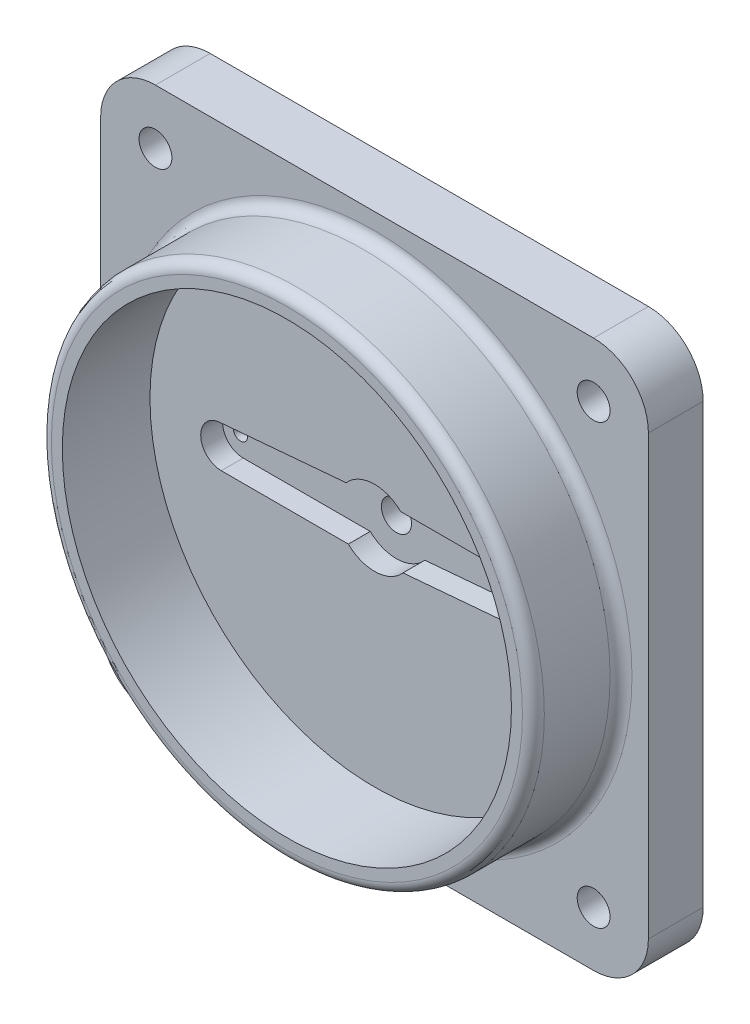
SolidWorks part; units mm, degrees
ref_plane "Plan de face" through (0, 0, 0) normal (0, 0, 1) x (1, 0, 0)
ref_plane "Plan de dessus" through (0, 0, 0) normal (0, 1, 0) x (1, 0, 0)
ref_plane "Plan de droite" through (0, 0, 0) normal (1, 0, 0) x (0, 0, -1)
sketch "Esquisse1" plane through (0, 0, 0) normal (0, 0, 1) x (1, 0, 0)
  line L1 (-25, 25) -> (25, 25)
  line L2 (-25, 25) -> (-25, -25)
  line L3 (-25, -25) -> (25, -25)
  line L4 (25, 25) -> (25, -25)
  line L5 (-25, 25) -> (25, -25) construction
  line L6 (-25, -25) -> (25, 25) construction
  point P0 (0, 0)
  dimension "D1" = 50
  dimension "D2" = 50
extrude "Boss.-Extru.3" add sketch "Esquisse1" along normal blind 5
sketch "Esquisse3" plane through (0, 0, 5) normal (0, 0, 1) x (1, 0, 0)
  circle A0 centre (0, 0) radius 22.5
  circle A1 centre (0, 0) radius 20.5
  dimension "D1" = 45
  dimension "D2" = 2
extrude "Boss.-Extru.4" add sketch "Esquisse3" along normal blind 8
sketch "Esquisse4" plane through (0, 0, 5) normal (0, 0, 1) x (1, 0, 0)
  line L0 (-14.1481, 1.2731) -> (-2.5947, 2.2661)
  line L1 (-13.9871, -2.48) -> (-2.3912, -2.48)
  line L2 (13.9871, 2.48) -> (2.3912, 2.48)
  line L3 (2.5947, -2.2661) -> (14.1134, -1.2758)
  line L4 (2.5947, -2.2661) -> (14.1481, -1.2731) construction
  arc A0 (-14.1481, 1.2731) -> (-13.9871, -2.48) centre (-13.9871, -0.6) ccw
  arc A1 (-2.3912, -2.48) -> (2.5947, -2.2661) centre (0, 0) ccw
  arc A2 (14.1134, -1.2758) -> (13.9871, 2.48) centre (13.9871, 0.6) ccw
  arc A3 (2.3912, 2.48) -> (-2.5947, 2.2661) centre (0, 0) ccw
  spline S0 degree 3 poles (2.3912, 2.48) (2.3342, 2.5074) (2.2739, 2.5344) (2.1936, 2.5683) (2.168, 2.5787) (2.128, 2.5946) (2.1141, 2.6) (2.1141, 2.6) knots 0.000153 0.000153 0.000153 0.000153 0.000392 0.000392 0.000511 0.000511 0.00063 0.00063 0.00063 0.00063 weights 1 1 1 1 1 1 1 1 construction
extrude "Enlèv. mat.-Extru.1" cut sketch "Esquisse4" against normal blind 2
sketch "Esquisse5" plane through (0, 0, 3) normal (0, 0, 1) x (1, 0, 0)
  circle A0 centre (-14.2369, -0.6107) radius 0.65
  circle A2 centre (14.2369, 0.6107) radius 0.65
  circle A3 centre (0, 0) radius 1.375
extrude "Enlèv. mat.-Extru.2" cut sketch "Esquisse5" against normal through all
fillet "Congé1" radius 5 4 edges at (25, 25, 2.5) (25, -25, 2.5) (-25, -25, 2.5) (-25, 25, 2.5)
sketch "Esquisse6" plane through (0, 0, 5) normal (0, 0, 1) x (1, 0, 0)
  line L0 (-25, -13.2288) -> (-25, -20)
  line L4 (25, -20) -> (25, 20)
  line L5 (20, 25) -> (-20, 25)
  line L6 (-25, 20) -> (-25, -20)
  line L7 (-20, -25) -> (20, -25)
  line L8 (25, -20) -> (25, 20)
  line L9 (20, 25) -> (-20, 25)
  line L11 (-20, -25) -> (20, -25)
  circle A0 centre (-20, 20) radius 1.5
  circle A1 centre (0, 0) radius 28.2843 construction
  circle A2 centre (20, 20) radius 1.5
  circle A3 centre (20, -20) radius 1.5
  arc A4 (25, 20) -> (20, 25) centre (20, 20) ccw
  arc A5 (-20, 25) -> (-25, 20) centre (-20, 20) ccw
  arc A6 (-25, -20) -> (-20, -25) centre (-20, -20) ccw
  arc A7 (20, -25) -> (25, -20) centre (20, -20) ccw
  arc A8 (25, 20) -> (20, 25) centre (20, 20) ccw
  arc A10 (-25, -20) -> (-20, -25) centre (-20, -20) ccw
  arc A11 (20, -25) -> (25, -20) centre (20, -20) ccw
  circle A12 centre (-20, -20) radius 1.5
  point P25 (0, 0)
  dimension "D2" = 3
  dimension "D1" = 0
  dimension "D3" = 4
extrude "Enlèv. mat.-Extru.3" cut sketch "Esquisse6" against normal through all contours A12 | A3 | A2 | A0
fillet "Congé2" radius 1 1 edges at (22.5, 0, 5)
fillet "Congé3" radius 1 1 edges at (22.5, 0, 13)
